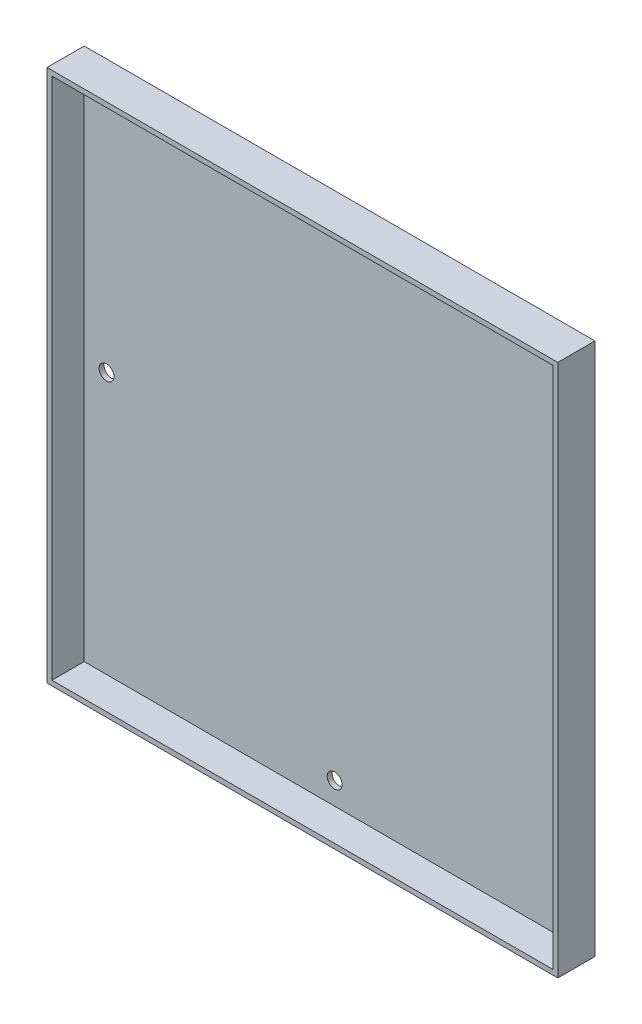
SolidWorks part; units mm, degrees
ref_plane "前视基准面" through (0, 0, 0) normal (0, 0, 1) x (1, 0, 0)
ref_plane "上视基准面" through (0, 0, 0) normal (0, 1, 0) x (1, 0, 0)
ref_plane "右视基准面" through (0, 0, 0) normal (1, 0, 0) x (0, 0, -1)
other "Configuration Table"
sketch "草图1" plane through (0, 0, 0) normal (0, 0, 1) x (1, 0, 0)
  line L1 (-103, 107.5) -> (103, 107.5)
  line L2 (-103, 107.5) -> (-103, -107.5)
  line L3 (-103, -107.5) -> (103, -107.5)
  line L4 (103, 107.5) -> (103, -107.5)
  line L5 (-103, 107.5) -> (103, -107.5) construction
  line L6 (-103, -107.5) -> (103, 107.5) construction
  point P0 (0, 0)
  dimension "D1" = 215
  dimension "D2" = 206
extrude "凸台-拉伸1" add sketch "草图1" along normal blind 15
shell "抽壳1" thickness 2
sketch "草图2" plane through (0, 0, 2) normal (0, 0, 1) x (1, 0, 0)
  line L0 (-101, 0) -> (0, 0) construction
  line L1 (-101, 105.5) -> (-101, -105.5) construction
  line L2 (0, 0) -> (0, 105.5) construction
  line L3 (101, 105.5) -> (-101, 105.5) construction
  circle A0 centre (-92, 0) radius 3
  circle A1 centre (0, 96.5) radius 3
  circle A2 centre (92, 0) radius 3
  circle A3 centre (0, -96.5) radius 3
  dimension "D1" = 6
  dimension "D2" = 193
  dimension "D3" = 184
extrude "切除-拉伸1" cut sketch "草图2" against normal blind 15
